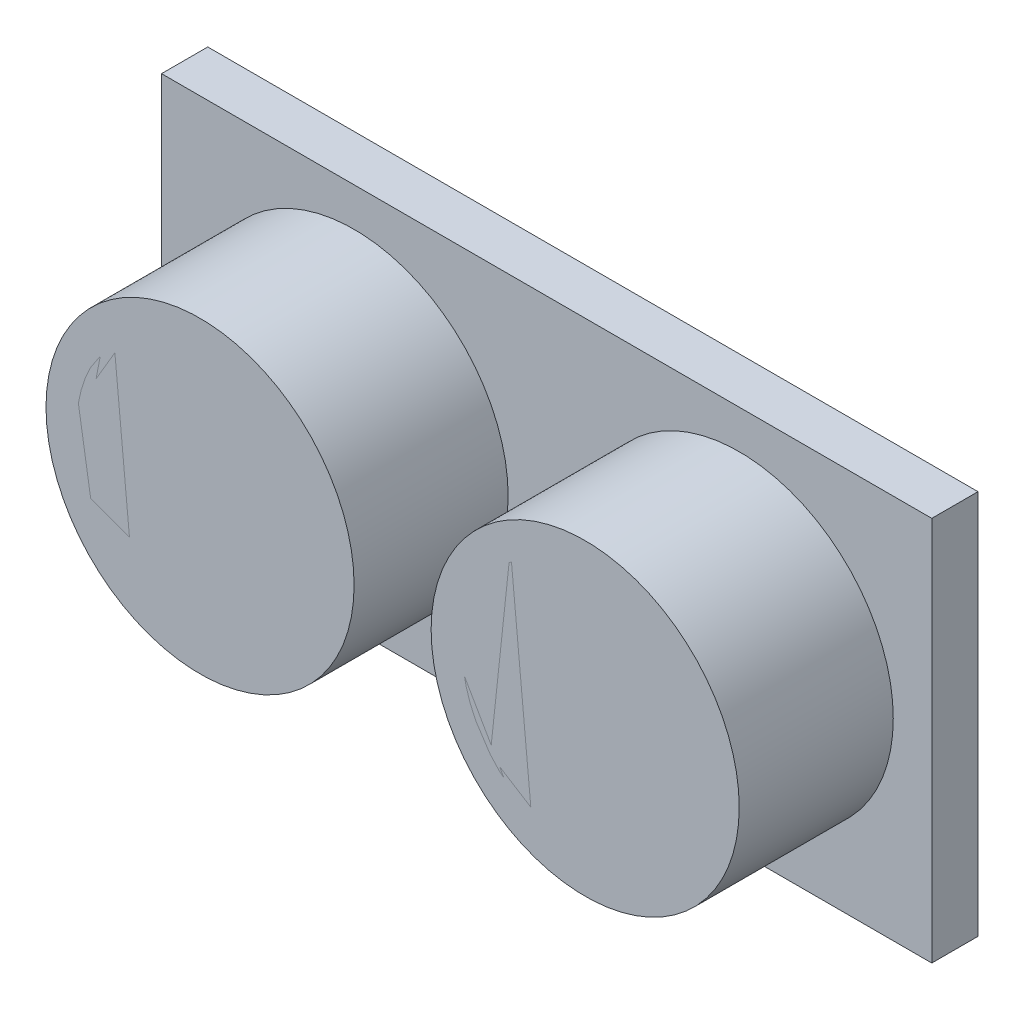
SolidWorks part; units mm, degrees
ref_plane "前视基准面" through (0, 0, 0) normal (0, 0, 1) x (1, 0, 0)
ref_plane "上视基准面" through (0, 0, 0) normal (0, 1, 0) x (1, 0, 0)
ref_plane "右视基准面" through (0, 0, 0) normal (1, 0, 0) x (0, 0, -1)
sketch "草图1" plane through (0, 0, 0) normal (0, 0, 1) x (1, 0, 0)
  line L1 (0, 0) -> (50, 0)
  line L2 (0, 0) -> (0, 25)
  line L3 (0, 25) -> (50, 25)
  line L4 (50, 0) -> (50, 25)
  dimension "D1" = 50
  dimension "D2" = 25
extrude "凸台-拉伸1" add sketch "草图1" along normal blind 3
sketch "草图2" plane through (0, 0, 3) normal (0, 0, 1) x (1, 0, 0)
  line L0 (0, 25) -> (0, 0) construction
  line L1 (50, 0) -> (50, 25) construction
  line L2 (0, 0) -> (50, 0) construction
  circle A0 centre (12.5, 12.5) radius 10
  circle A1 centre (37.5, 12.5) radius 10
  dimension "D1" = 20
  dimension "D2" = 12.5
  dimension "D3" = 12.5
  dimension "D4" = 12.5
extrude "凸台-拉伸2" add sketch "草图2" along normal blind 10
sketch "草图3" plane through (0, 0, 13) normal (0, 0, 1) x (1, 0, 0)
  circle A0 centre (12.5, 12.5) radius 8
  dimension "D1" = 16
extrude "凸台-拉伸3" add sketch "草图3" against normal blind 5 separate body
sketch "草图4" plane through (0, 0, 13) normal (0, 0, 1) x (1, 0, 0)
  circle A0 centre (37.5, 12.5) radius 8
  dimension "D1" = 16
extrude "凸台-拉伸4" add sketch "草图4" against normal blind 5 separate body
